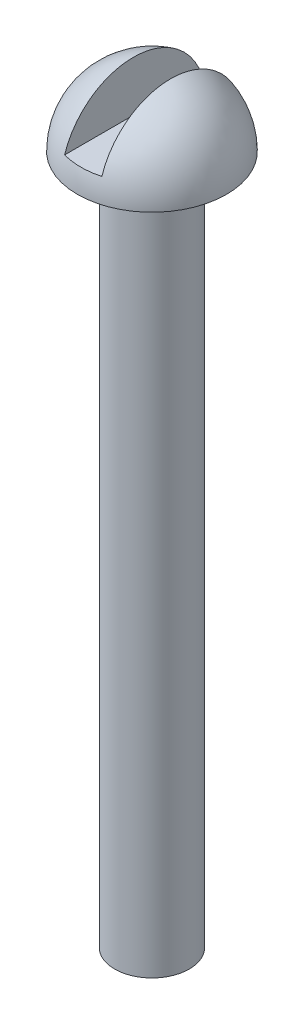
SolidWorks part; units mm, degrees
ref_plane "Front Plane" through (0, 0, 0) normal (0, 0, 1) x (1, 0, 0)
ref_plane "Top Plane" through (0, 0, 0) normal (0, 1, 0) x (1, 0, 0)
ref_plane "Right Plane" through (0, 0, 0) normal (1, 0, 0) x (0, 0, -1)
sketch "Sketch1" plane through (0, 0, 0) normal (0, 1, 0) x (1, 0, 0)
  circle A0 centre (0, 0) radius 2
  dimension "D1" = 4
extrude "Boss-Extrude1" add sketch "Sketch1" along normal blind 37
sketch "Sketch2" plane through (0, 0, 0) normal (0, 0, 1) x (1, 0, 0)
  line L0 (0, 41) -> (0, 37)
  line L1 (2, 37) -> (-2, 37) construction
  line L2 (0, 37) -> (4, 37)
  line L3 (0, 37) -> (0, 35.4598) construction
  arc A0 (0, 41) -> (4, 37) centre (0, 37) cw
  point P5 (0, 0)
  dimension "D1" = 4
revolve "Revolve1" add sketch "Sketch2" angle 360 about L3
sketch "Sketch3" plane through (0, 0, 0) normal (0, 0, 1) x (1, 0, 0)
  line L0 (-1, 41.3066) -> (-1, 38.18)
  line L1 (-1, 38.18) -> (1, 38.18)
  line L2 (1, 38.18) -> (1, 41.3066)
  line L3 (1, 41.3066) -> (-1, 41.3066)
  line L4 (0, 34.6) -> (0, 41.8) construction
  line L5 (-2, 37) -> (2, 37) construction
  point P2 (0, 38.18)
  point P9 (0, 0)
  point P10 (-1, 41.3066)
  dimension "D1" = 2
  dimension "D2" = 1.18
extrude "Cut-Extrude1" cut sketch "Sketch3" against normal through all both and the other way through all
